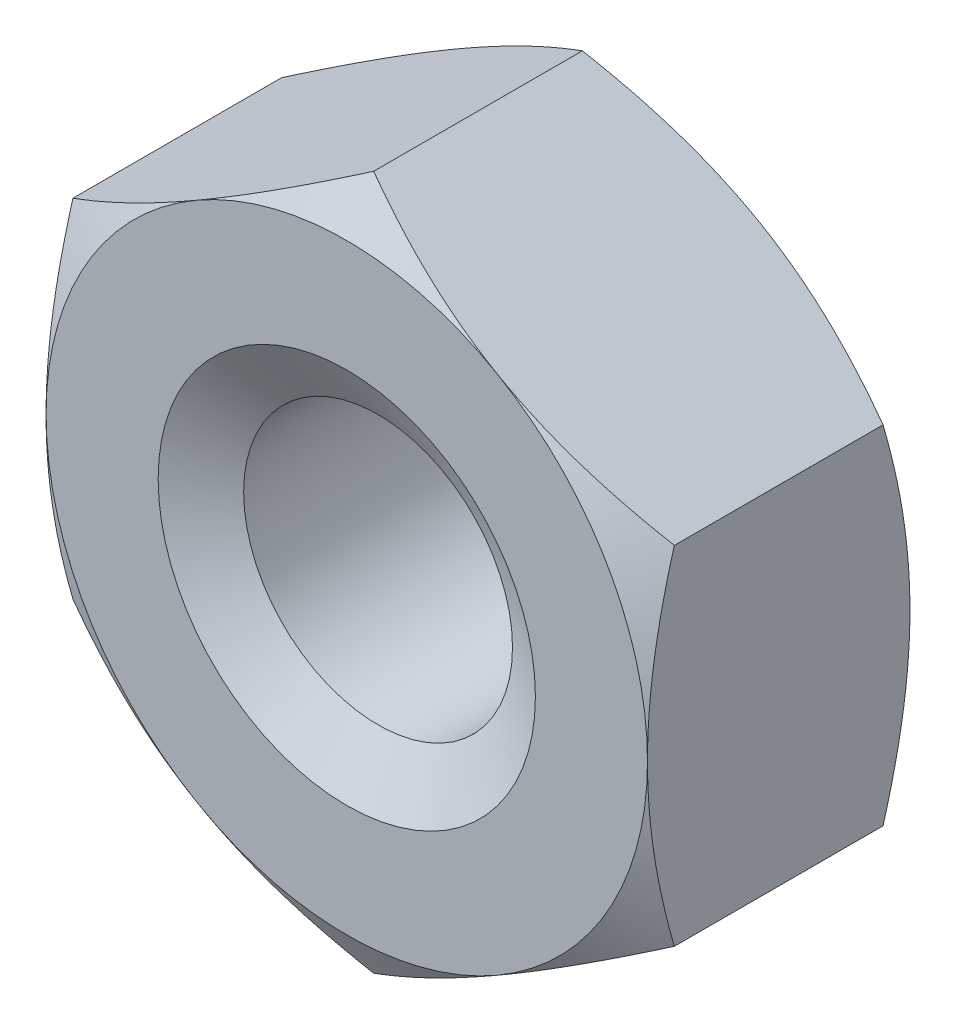
SolidWorks part; units mm, degrees
ref_plane "前视基准面" through (0, 0, 0) normal (0, 0, 1) x (1, 0, 0)
ref_plane "上视基准面" through (0, 0, 0) normal (0, 1, 0) x (1, 0, 0)
ref_plane "右视基准面" through (0, 0, 0) normal (1, 0, 0) x (0, 0, -1)
sketch "草图1" plane through (0, 0, 0) normal (1, 0, 0) x (0, 0, -1)
  line L0 (0, 3.005) -> (0, -3.005) construction
  line L1 (0, 0) -> (2.4, 0) construction
  line L2 (0, 0) -> (0, 3.005)
  line L3 (0, 3.005) -> (2.4, 3.005)
  line L4 (2.4, 3.005) -> (2.4, 0)
  line L5 (0, 1.5) -> (2.4, 1.5)
  line L6 (0, 1.2294) -> (2.4, 1.2294)
  line L7 (2, 3.005) -> (2, 0)
  line L8 (0, 2.75) -> (0.1472, 3.005)
  line L9 (0, 1.5) -> (0.1562, 1.2294)
  line L10 (0, -1.5) -> (0.1562, -1.2294)
  line L11 (2, 2.3) -> (2.4, 2.3)
  point P5 (0.7, 0)
  point P10 (1.9, 0)
  point P22 (0, 3.45)
  dimension "e" = 6.01
  dimension "m" = 2.4
  dimension "mw" = 1.7
  dimension "D" = 3
  dimension "P" = 0.5
  dimension "D81" = 2.4588
  dimension "c" = 0.4
  dimension "β" = 30
  dimension "s" = 5.5
  dimension "θ" = 120
  dimension "dw" = 4.6
  dimension "da" = 3.45
sketch "草图2" plane through (0, 0, 0) normal (0, 0, 1) x (1, 0, 0)
  line L1 (0, 3.1754) -> (-2.75, 1.5877)
  line L2 (-2.75, 1.5877) -> (-2.75, -1.5877)
  line L3 (-2.75, -1.5877) -> (0, -3.1754)
  line L4 (0, -3.1754) -> (2.75, -1.5877)
  line L5 (2.75, -1.5877) -> (2.75, 1.5877)
  line L6 (2.75, 1.5877) -> (0, 3.1754)
  circle A0 centre (0, 0) radius 2.75 construction
  circle A1 centre (0, 0) radius 1.2294
  dimension "D1" = 5.5
sketch "草图3" plane through (0, 0, 0) normal (0, 0, 1) x (1, 0, 0)
  line L0 (0, 3.1754) -> (-2.75, 1.5877) construction
  line L1 (2.75, 1.5877) -> (0, 3.1754) construction
  line L2 (2.75, -1.5877) -> (2.75, 1.5877) construction
  line L3 (0, -3.1754) -> (2.75, -1.5877) construction
  line L4 (-2.75, -1.5877) -> (0, -3.1754) construction
  line L5 (-2.75, 1.5877) -> (-2.75, -1.5877) construction
  line L6 (0, 3.1754) -> (-2.75, 1.5877)
  line L7 (2.75, 1.5877) -> (0, 3.1754)
  line L8 (2.75, -1.5877) -> (2.75, 1.5877)
  line L9 (0, -3.1754) -> (2.75, -1.5877)
  line L10 (-2.75, -1.5877) -> (0, -3.1754)
  line L11 (-2.75, 1.5877) -> (-2.75, -1.5877)
  circle A0 centre (0, 0) radius 1.2294 construction
  circle A1 centre (0, 0) radius 1.2294
extrude "凸台-拉伸1" add sketch "草图3" against normal up to vertex (2.4 mm away) up to point (0, 0, -2.4)
cosmetic thread "装饰螺纹线1" parameters "D2"=3
sketch "草图4" plane through (0, 0, 0) normal (1, 0, 0) x (0, 0, -1)
  line L1 (0, 1.725) -> (0.2861, 1.2294)
  line L2 (0, 0) -> (2.4, 0) construction
  line L3 (0, 0) -> (2.4, 0) construction
  line L4 (1.2, 0) -> (1.2, 3.005) construction
  line L5 (0, 3.005) -> (2.4, 3.005) construction
  line L6 (0.2861, 1.2294) -> (0.2861, 0)
  line L7 (0.2861, 0) -> (0, 0)
  line L8 (0, 0) -> (0, 1.725)
  line L9 (2.4, 0) -> (2.4, 1.725)
  line L10 (2.1139, 0) -> (2.4, 0)
  line L11 (2.1139, 1.2294) -> (2.1139, 0)
  line L12 (2.4, 1.725) -> (2.1139, 1.2294)
  line L16 (0, 1.5) -> (0.1562, 1.2294) construction
  line L17 (0, 1.2294) -> (2.4, 1.2294) construction
  dimension "D1" = 3.45
revolve "切除-旋转1" cut sketch "草图4" angle 360 mid plane about L3
sketch "草图5" plane through (0, 0, 0) normal (0, 0, 1) x (1, 0, 0)
  circle A0 centre (0, 0) radius 2.75
  circle A1 centre (0, 0) radius 4.5075
  circle A2 centre (0, 0) radius 2.75 construction
  dimension "D1" = 9.015
extrude "切除-拉伸1" cut sketch "草图5" against normal blind 0.48 draft 60
sketch "草图7" plane through (0, 0, -2.4) normal (0, 0, -1) x (-1, 0, 0)
  circle A1 centre (0, 0) radius 4.5075
  circle A2 centre (0, 0) radius 4.5075
  circle A3 centre (0, 0) radius 2.75
  circle A4 centre (0, 0) radius 2.75
  dimension "D1" = 0
  dimension "D2" = 0
extrude "切除-拉伸2" cut sketch "草图7" against normal blind 0.48 draft 60
sketch "草图6" [suppressed] plane through (0, 0, 0) normal (1, 0, 0) x (0, 0, -1)
  line L0 (51, 44.1) -> (50, 44.1)
  line L1 (50, 44.1) -> (50, 54.8483)
  line L2 (50, 54.8483) -> (51, 54.8483)
  line L3 (51, 54.8483) -> (51, 44.1)
  line L4 (0, 0) -> (51, 0) construction
  line L5 (0, 0) -> (51, 0) construction
  line L6 (46.7575, 54.8483) -> (4.2425, 54.8483) construction
revolve "切除-旋转2" [suppressed] cut sketch "草图6" angle 360 mid plane about L5
